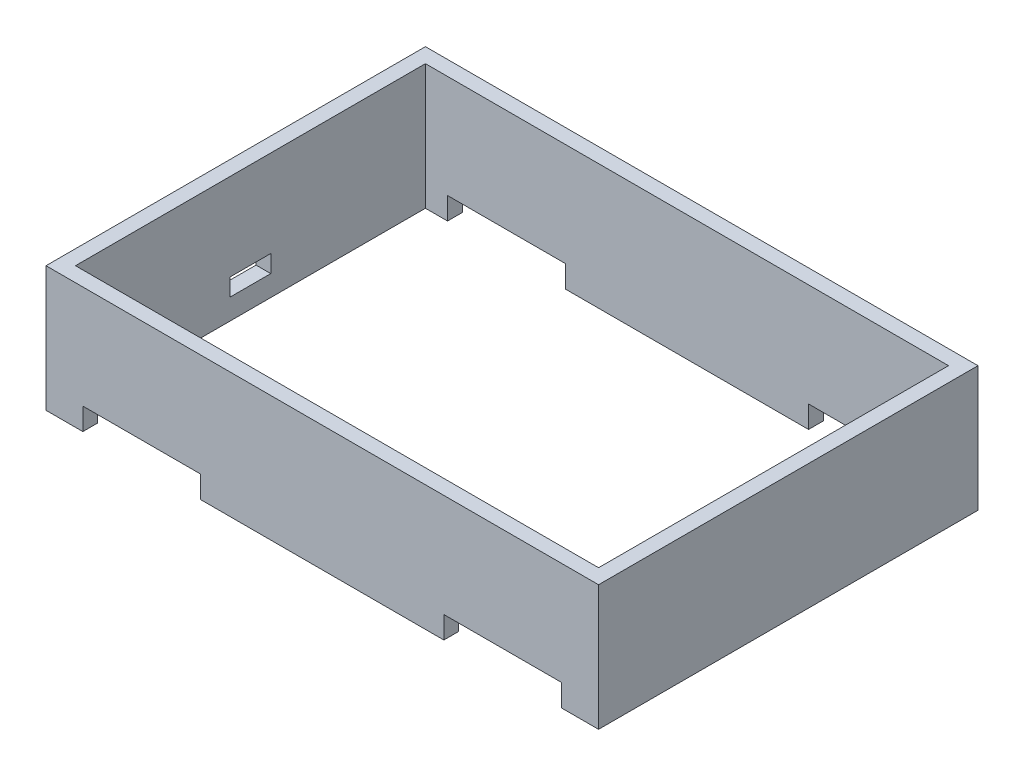
SolidWorks part; units mm, degrees
ref_plane "Front Plane" through (0, 0, 0) normal (0, 0, 1) x (1, 0, 0)
ref_plane "Top Plane" through (0, 0, 0) normal (0, 1, 0) x (1, 0, 0)
ref_plane "Right Plane" through (0, 0, 0) normal (1, 0, 0) x (0, 0, -1)
sketch "Sketch1" plane through (0, 0, 0) normal (0, 1, 0) x (1, 0, 0)
  line L1 (-47.625, 32.7025) -> (47.625, 32.7025)
  line L2 (-47.625, 32.7025) -> (-47.625, -32.7025)
  line L3 (-47.625, -32.7025) -> (47.625, -32.7025)
  line L4 (47.625, 32.7025) -> (47.625, -32.7025)
  line L5 (-47.625, 32.7025) -> (47.625, -32.7025) construction
  line L6 (-47.625, -32.7025) -> (47.625, 32.7025) construction
  point P0 (0, 0)
  dimension "D1" = 65.405
  dimension "D2" = 95.25
extrude "Boss-Extrude1" add sketch "Sketch1" along normal blind 21.59
sketch "Sketch2" plane through (0, 21.59, 0) normal (0, 1, 0) x (1, 0, 0)
  line L0 (-45.085, 30.1625) -> (-45.085, 32.7025) construction
  line L1 (45.085, -30.1625) -> (-45.085, -30.1625)
  line L2 (45.085, -30.1625) -> (45.085, 30.1625)
  line L3 (45.085, 30.1625) -> (-45.085, 30.1625)
  line L4 (-45.085, -30.1625) -> (-45.085, 30.1625)
  line L5 (47.625, -30.1625) -> (45.085, -30.1625) construction
  line L6 (-45.085, 30.1625) -> (-47.625, 30.1625) construction
  line L7 (47.625, 32.7025) -> (-47.625, 32.7025) construction
  line L8 (47.625, -32.7025) -> (47.625, 32.7025) construction
  line L9 (45.085, -32.7025) -> (45.085, -30.1625) construction
  line L10 (-47.625, -32.7025) -> (47.625, -32.7025) construction
  line L11 (-47.625, 32.7025) -> (-47.625, -32.7025) construction
  point P0 (0, 0)
  dimension "D1" = 2.54
extrude "Cut-Extrude1" cut sketch "Sketch2" against normal up to surface (21.59 mm away) up to face at (0, 0, 0)
sketch "Sketch3" plane through (-47.625, 0, 0) normal (-1, 0, 0) x (0, 0, 1)
  line L0 (0, 5.08) -> (0, 0) construction
  line L1 (3.5, 3.58) -> (-3.5, 3.58)
  line L2 (3.5, 3.58) -> (3.5, 6.58)
  line L3 (3.5, 6.58) -> (-3.5, 6.58)
  line L4 (-3.5, 3.58) -> (-3.5, 6.58)
  line L5 (3.5, 3.58) -> (-3.5, 6.58) construction
  line L6 (3.5, 6.58) -> (-3.5, 3.58) construction
  point P0 (0, 5.08)
  dimension "D1" = 3
  dimension "D2" = 7
  dimension "D3" = 5.08
extrude "Cut-Extrude2" cut sketch "Sketch3" against normal up to next
sketch "Sketch4" plane through (0, 0, -32.7025) normal (0, 0, -1) x (-1, 0, 0)
  line L0 (0, 0) -> (0, 21.59) construction
  line L1 (-20.955, 0) -> (-41.275, 0)
  line L2 (-20.955, 0) -> (-20.955, 3.81)
  line L3 (-20.955, 3.81) -> (-41.275, 3.81)
  line L4 (-41.275, 0) -> (-41.275, 3.81)
  line L5 (-20.955, 0) -> (-41.275, 3.81) construction
  line L6 (-20.955, 3.81) -> (-41.275, 0) construction
  line L7 (41.275, 0) -> (20.955, 0)
  line L8 (41.275, 0) -> (41.275, 3.81)
  line L9 (41.275, 3.81) -> (20.955, 3.81)
  line L10 (20.955, 0) -> (20.955, 3.81)
  line L11 (41.275, 0) -> (20.955, 3.81) construction
  line L12 (41.275, 3.81) -> (20.955, 0) construction
  line L13 (-47.625, 0) -> (47.625, 0) construction
  line L14 (-47.625, 21.59) -> (47.625, 21.59) construction
  line L15 (-31.115, 1.905) -> (31.115, 1.905) construction
  line L16 (-47.625, 21.59) -> (-47.625, 0) construction
  point P0 (-31.115, 1.905)
  point P5 (31.115, 1.905)
  point P18 (0, 1.905)
  point P19 (-25.8919, 5.8036)
  point P20 (16.9977, 1.653)
  point P21 (-29.4496, 4.6177)
  point P22 (-33.9283, 3.81)
  dimension "D1" = 20.32
  dimension "D2" = 3.81
  dimension "D3" = 6.35
extrude "Cut-Extrude3" cut sketch "Sketch4" against normal through all both and the other way through all
equation "\"`\"=4.125"
